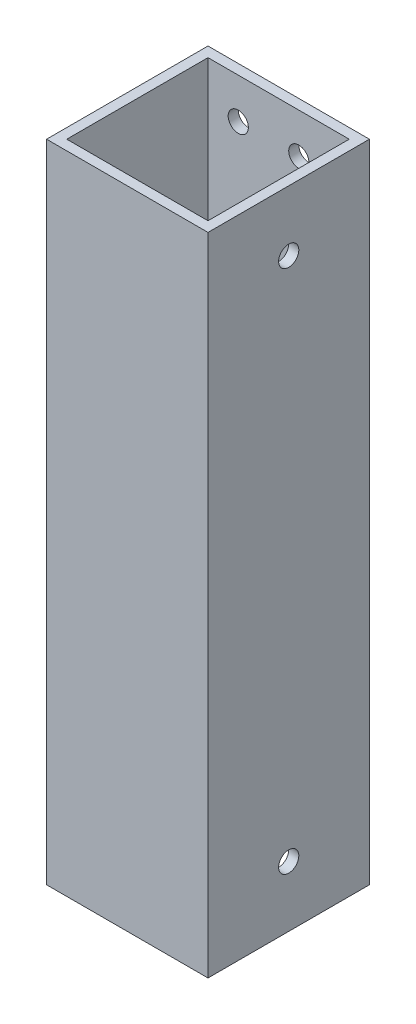
SolidWorks part; units mm, degrees
ref_plane "Front Plane" through (0, 0, 0) normal (0, 0, 1) x (1, 0, 0)
ref_plane "Top Plane" through (0, 0, 0) normal (0, 1, 0) x (1, 0, 0)
ref_plane "Right Plane" through (0, 0, 0) normal (1, 0, 0) x (0, 0, -1)
sketch "Sketch1" plane through (0, 0, 0) normal (0, 1, 0) x (1, 0, 0)
  line L1 (0, 0) -> (50.8, 0)
  line L2 (0, 0) -> (0, 50.8)
  line L3 (0, 50.8) -> (50.8, 50.8)
  line L4 (50.8, 0) -> (50.8, 50.8)
  line L5 (3.175, 3.175) -> (47.625, 3.175)
  line L6 (3.175, 3.175) -> (3.175, 47.625)
  line L7 (3.175, 47.625) -> (47.625, 47.625)
  line L8 (47.625, 3.175) -> (47.625, 47.625)
  dimension "D1" = 50.8
  dimension "D2" = 50.8
  dimension "D3" = 3.175
  dimension "D4" = 3.175
  dimension "D5" = 3.175
  dimension "D6" = 3.175
extrude "Boss-Extrude1" add sketch "Sketch1" along normal blind 203.2
sketch "Sketch2" plane through (0, 0, -50.8) normal (0, 0, -1) x (-1, 0, 0)
  line L0 (-50.8, 203.2) -> (0, 203.2) construction
  line L1 (-50.8, 203.2) -> (-50.8, 0) construction
  circle A0 centre (-12.7, 190.5) radius 3.175
  circle A1 centre (-31.75, 190.5) radius 3.175
  circle A2 centre (-31.75, 12.7) radius 3.175
  circle A3 centre (-12.7, 12.7) radius 3.175
  dimension "D1" = 12.7
  dimension "D2" = 12.7
  dimension "D3" = 190.5
  dimension "D4" = 190.5
  dimension "D5" = 19.05
  dimension "D6" = 38.1
  dimension "D7" = 38.1
  dimension "D8" = 19.05
extrude "Cut-Extrude1" cut sketch "Sketch2" against normal blind 24.638
sketch "Sketch3" plane through (50.8, 0, 0) normal (1, 0, 0) x (0, 0, -1)
  line L0 (0, 203.2) -> (0, 0) construction
  line L1 (0, 0) -> (50.8, 0) construction
  circle A0 centre (25.4, 184.15) radius 3.175
  circle A1 centre (25.4, 19.05) radius 3.175
  dimension "D1" = 25.4
  dimension "D2" = 25.4
  dimension "D3" = 19.05
  dimension "D4" = 184.15
extrude "Cut-Extrude2" cut sketch "Sketch3" against normal blind 24.638
